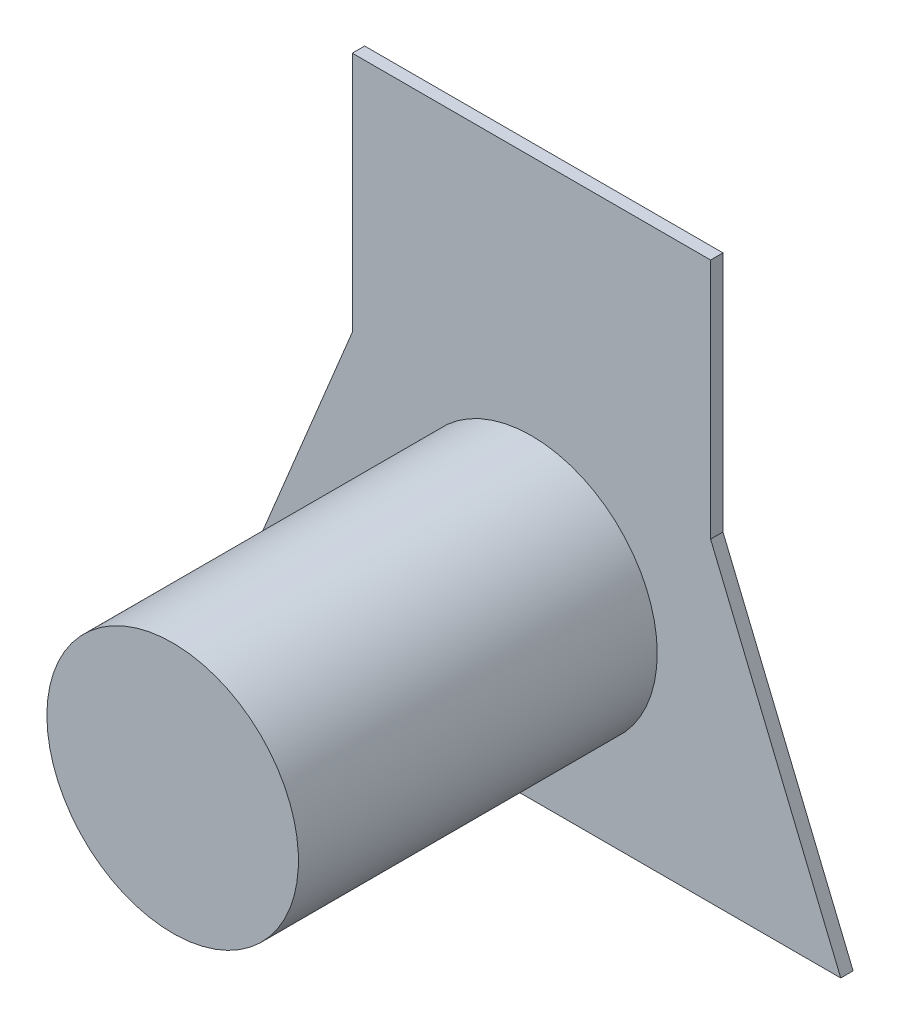
SolidWorks part; units mm, degrees
ref_plane "前视基准面" through (0, 0, 0) normal (0, 0, 1) x (1, 0, 0)
ref_plane "上视基准面" through (0, 0, 0) normal (0, 1, 0) x (1, 0, 0)
ref_plane "右视基准面" through (0, 0, 0) normal (1, 0, 0) x (0, 0, -1)
sketch "草图1" plane through (0, 0, 0) normal (0, 0, 1) x (1, 0, 0)
  line L0 (-50, 0) -> (-28.9609, 50.9221)
  line L1 (-50, 0) -> (50, 0)
  line L2 (-28.9609, 90) -> (28.9609, 90)
  line L3 (26.5946, 90) -> (28.9609, 92.7805) construction
  line L6 (28.9609, 50.9221) -> (28.9609, 90)
  line L7 (-28.9609, 50.9221) -> (-28.9609, 90)
  line L9 (50, 0) -> (28.9609, 50.9221)
  point P0 (5.3461, 65.0326)
  dimension "D1" = 90
  dimension "D2" = 100
extrude "凸台-拉伸1" add sketch "草图1" along normal blind 2
sketch "草图3" plane through (0, 0, 0) normal (0, 0, -1) x (-1, 0, 0)
  circle A0 centre (0, 30.5962) radius 20.3335
extrude "凸台-拉伸2" add sketch "草图3" against normal blind 60
